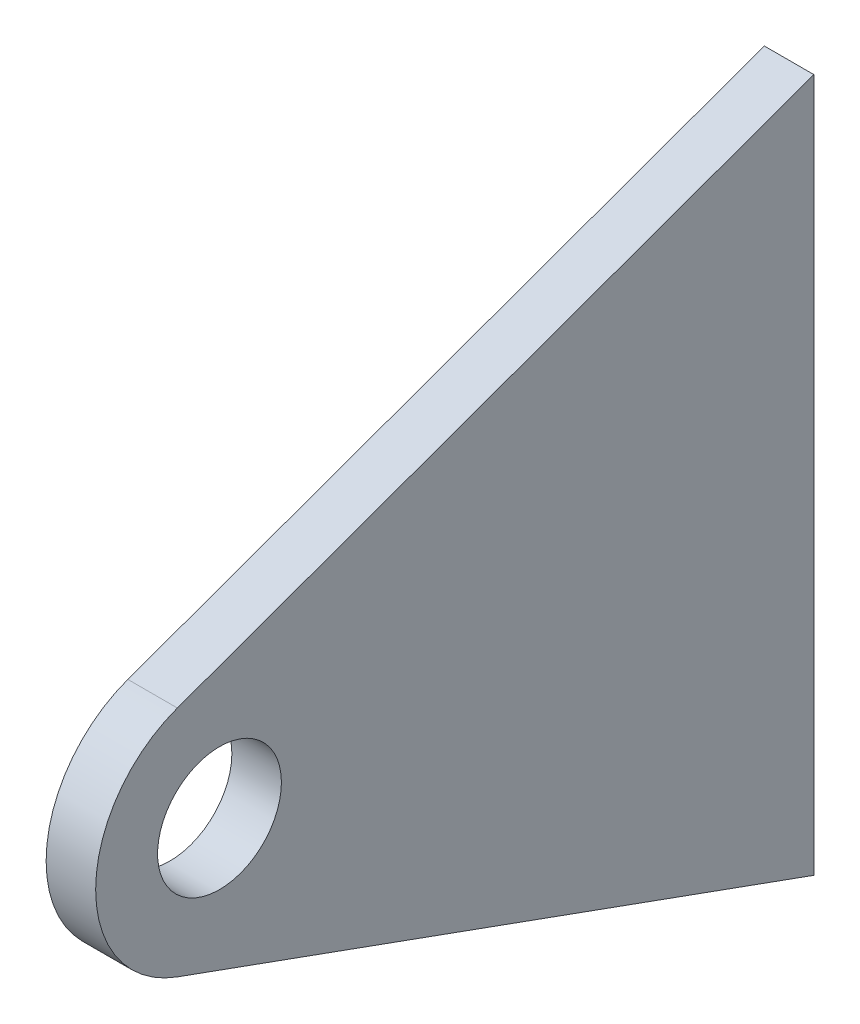
SolidWorks part; units mm, degrees
ref_plane "Front Plane" through (0, 0, 0) normal (1, 0, 0) x (0, 1, 0)
ref_plane "Top Plane" through (0, 0, 0) normal (0, 0, 1) x (0, 1, 0)
ref_plane "Right Plane" through (0, 0, 0) normal (0, 1, 0) x (-1, 0, 0)
sketch "Sketch2" plane through (0, 0, 0) normal (1, 0, 0) x (0, 1, 0)
  line L0 (0, 0) -> (0, 240) construction
  line L1 (0, 0) -> (140, 0)
  line L2 (140, 0) -> (47.0176, 257.0102)
  line L3 (0, 0) -> (-140, 0)
  line L4 (-140, 0) -> (-47.0176, 257.0102)
  arc A0 (47.0176, 257.0102) -> (-47.0176, 257.0102) centre (0, 240) ccw
  circle A1 centre (0, 240) radius 25
  dimension "D3" = 50
  dimension "D4" = 50
  dimension "D1" = 280
  dimension "D2" = 240
extrude "Boss-Extrude1" add sketch "Sketch2" along normal mid plane 20
